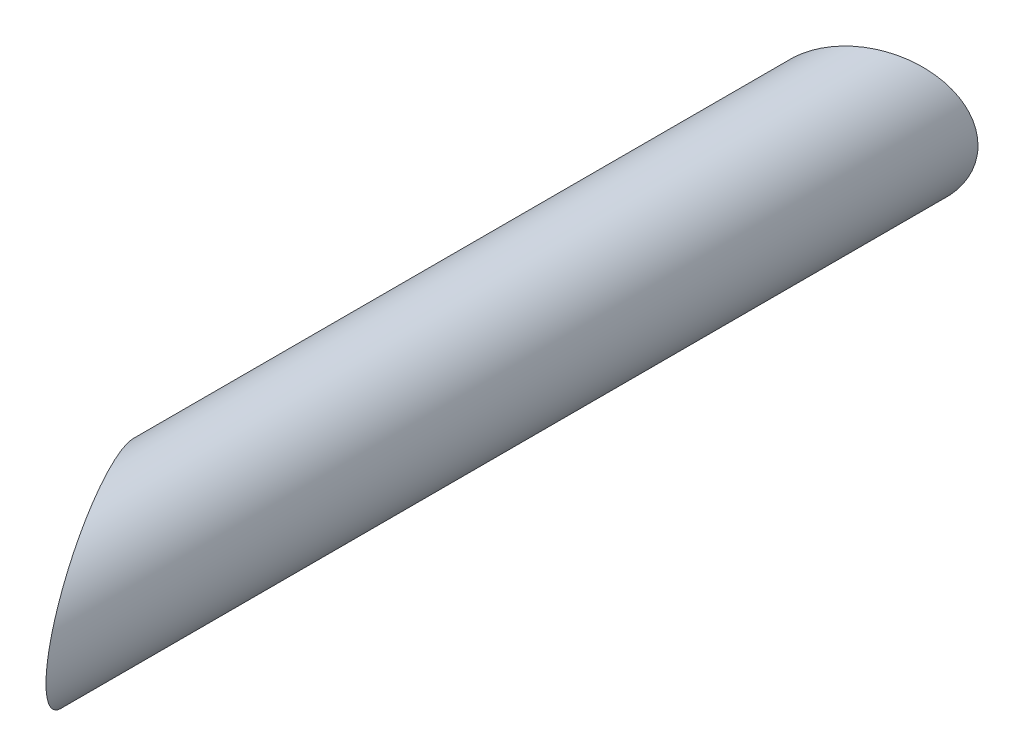
SolidWorks part; units mm, degrees
ref_plane "Front Plane" through (0, 0, 0) normal (0, 0, 1) x (1, 0, 0)
ref_plane "Top Plane" through (0, 0, 0) normal (0, 1, 0) x (1, 0, 0)
ref_plane "Right Plane" through (0, 0, 0) normal (1, 0, 0) x (0, 0, -1)
sketch "Sketch2" plane through (0, 0, 0) normal (0, 0, 1) x (1, 0, 0)
  circle A0 centre (0, 0) radius 7.5
  point P3 (0, 0)
  dimension "D1" = 15
extrude "Boss-Extrude1" add sketch "Sketch2" along normal blind 100
sketch "Sketch3" plane through (0, 0, 0) normal (0, 1, 0) x (1, 0, 0)
  line L0 (7.5, 0) -> (-16.6002, -13.9142)
  line L1 (-16.6002, -13.9142) -> (-16.6002, 6.796)
  line L2 (7.5, 0) -> (7.5, 6.796)
  line L3 (7.5, 6.796) -> (-16.6002, 6.796)
  line L4 (7.5, -100) -> (-10.5, -68.8231)
  line L5 (-10.5, -68.8231) -> (-10.5, -108.8231)
  line L6 (-10.5, -108.8231) -> (7.5, -108.8231)
  line L7 (7.5, -108.8231) -> (7.5, -100)
  line L8 (7.5, 0) -> (-7.5, 0) construction
  line L9 (-7.5, -100) -> (7.5, -100) construction
  dimension "D1" = 30
  dimension "D2" = 60
  dimension "D3" = 40
  dimension "D4" = 18
extrude "Cut-Extrude1" cut sketch "Sketch3" against normal mid plane 100
sketch "Sketch5" plane through (1.875, 0, 3.2476) normal (-0.5, 0, -0.866) x (-0.866, 0, 0.5)
  circle A0 centre (4.8253, 0) radius 2.5
  ellipse E0 centre (2.1651, 0) end of major axis (-6.4952, 0) minor radius 7.5 construction
  point P2 (10.8253, 0)
  dimension "D1" = 5
  dimension "D2" = 6
extrude "Cut-Extrude2" cut sketch "Sketch5" against normal blind 10
sketch "Sketch6" plane through (-37.6763, 0, 21.7524) normal (-0.866, 0, 0.5) x (0.5, 0, 0.866)
  circle A0 centre (68.3525, 0) radius 2.5
  ellipse E0 centre (75.3525, 0) end of major axis (60.3525, 0) minor radius 7.5 construction
  point P2 (60.3525, 0)
  dimension "D1" = 5
  dimension "D2" = 8
extrude "Cut-Extrude3" cut sketch "Sketch6" against normal blind 7
